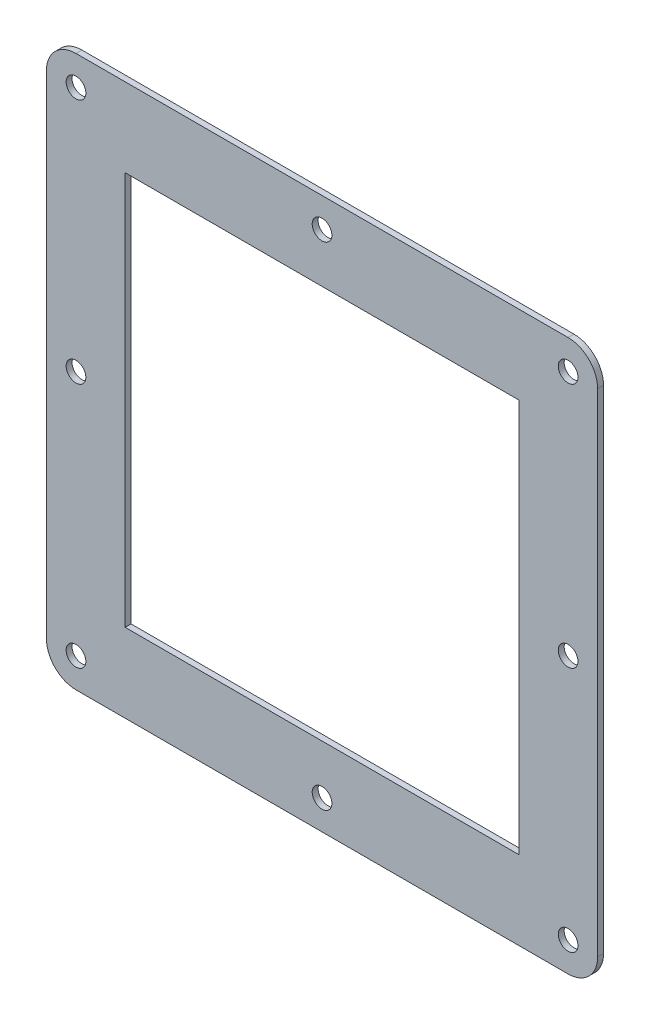
SolidWorks part; units mm, degrees
ref_plane "Front Plane" through (0, 0, 0) normal (0, 0, 1) x (1, 0, 0)
ref_plane "Top Plane" through (0, 0, 0) normal (0, 1, 0) x (1, 0, 0)
ref_plane "Right Plane" through (0, 0, 0) normal (1, 0, 0) x (0, 0, -1)
sketch "Sketch2" plane through (0, 0, 0) normal (0, 0, 1) x (1, 0, 0)
  line L0 (-125, 125) -> (125, 125) construction
  line L1 (-125, 140) -> (125, 140)
  line L2 (-140, 125) -> (-140, -125)
  line L3 (-125, -140) -> (125, -140)
  line L4 (140, 125) -> (140, -125)
  line L5 (-140, 140) -> (140, -140) construction
  line L6 (-140, -140) -> (140, 140) construction
  line L7 (125, 125) -> (125, -125) construction
  line L8 (125, -125) -> (-125, -125) construction
  line L9 (-125, -125) -> (-125, 125) construction
  arc A0 (-140, -125) -> (-125, -140) centre (-125, -125) ccw
  arc A1 (125, -140) -> (140, -125) centre (125, -125) ccw
  arc A2 (125, 140) -> (140, 125) centre (125, 125) cw
  arc A3 (-125, 140) -> (-140, 125) centre (-125, 125) ccw
  circle A4 centre (-125, 125) radius 5
  circle A5 centre (0, 125) radius 5
  circle A6 centre (125, 125) radius 5
  circle A13 centre (0, 0) radius 4
  circle A14 centre (125, 0) radius 5
  circle A15 centre (-125, 0) radius 5
  circle A16 centre (-125, -125) radius 5
  circle A17 centre (0, -125) radius 5
  circle A18 centre (125, -125) radius 5
  point P0 (0, 0)
  dimension "D3" = 15
  dimension "D4" = 10
  dimension "D5" = 10
  dimension "D6" = 10
  dimension "D7" = 8
  dimension "D8" = 10
  dimension "D9" = 10
  dimension "D10" = 10
  dimension "D11" = 10
  dimension "D1" = 280
  dimension "D2" = 280
extrude "Boss-Extrude1" add sketch "Sketch2" along normal blind 3
sketch "Sketch3" plane through (0, 0, 3) normal (0, 0, 1) x (1, 0, 0)
  line L1 (-100, 100) -> (100, 100)
  line L2 (-100, 100) -> (-100, -100)
  line L3 (-100, -100) -> (100, -100)
  line L4 (100, 100) -> (100, -100)
  line L5 (-100, 100) -> (100, -100) construction
  line L6 (-100, -100) -> (100, 100) construction
  point P0 (0, 0)
  dimension "D1" = 200
  dimension "D2" = 200
extrude "Cut-Extrude1" cut sketch "Sketch3" against normal blind 10
